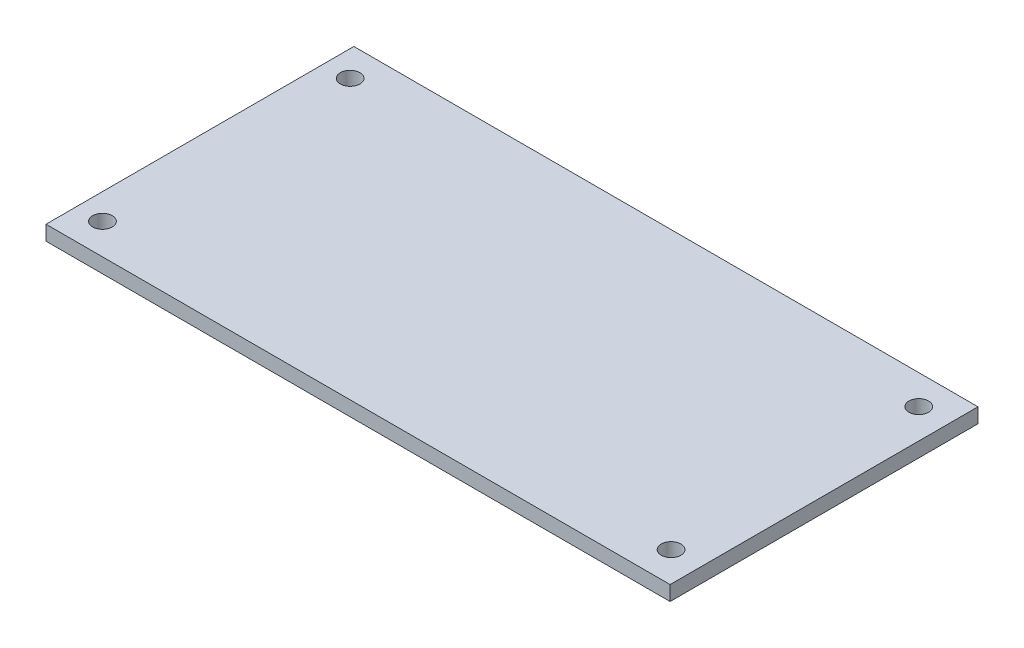
SolidWorks part; units mm, degrees
ref_plane "Front Plane" through (0, 0, 0) normal (0, 0, 1) x (1, 0, 0)
ref_plane "Top Plane" through (0, 0, 0) normal (0, 1, 0) x (1, 0, 0)
ref_plane "Right Plane" through (0, 0, 0) normal (1, 0, 0) x (0, 0, -1)
sketch "Sketch1" plane through (0, 0, 0) normal (0, 1, 0) x (1, 0, 0)
  line L1 (-63.6, 31.375) -> (63.6, 31.375)
  line L2 (-63.6, 31.375) -> (-63.6, -31.375)
  line L3 (-63.6, -31.375) -> (63.6, -31.375)
  line L4 (63.6, 31.375) -> (63.6, -31.375)
  line L5 (-63.6, 31.375) -> (63.6, -31.375) construction
  line L6 (-63.6, -31.375) -> (63.6, 31.375) construction
  circle A4 centre (57.531, 25.3683) radius 2
  circle A5 centre (57.531, -25.1142) radius 2
  circle A6 centre (-58.3565, -25.1142) radius 2
  circle A7 centre (-58.3565, 25.3683) radius 2
  point P0 (0, 0)
  dimension "D1" = 127.2
  dimension "D2" = 62.75
extrude "Boss-Extrude1" add sketch "Sketch1" along normal blind 3
